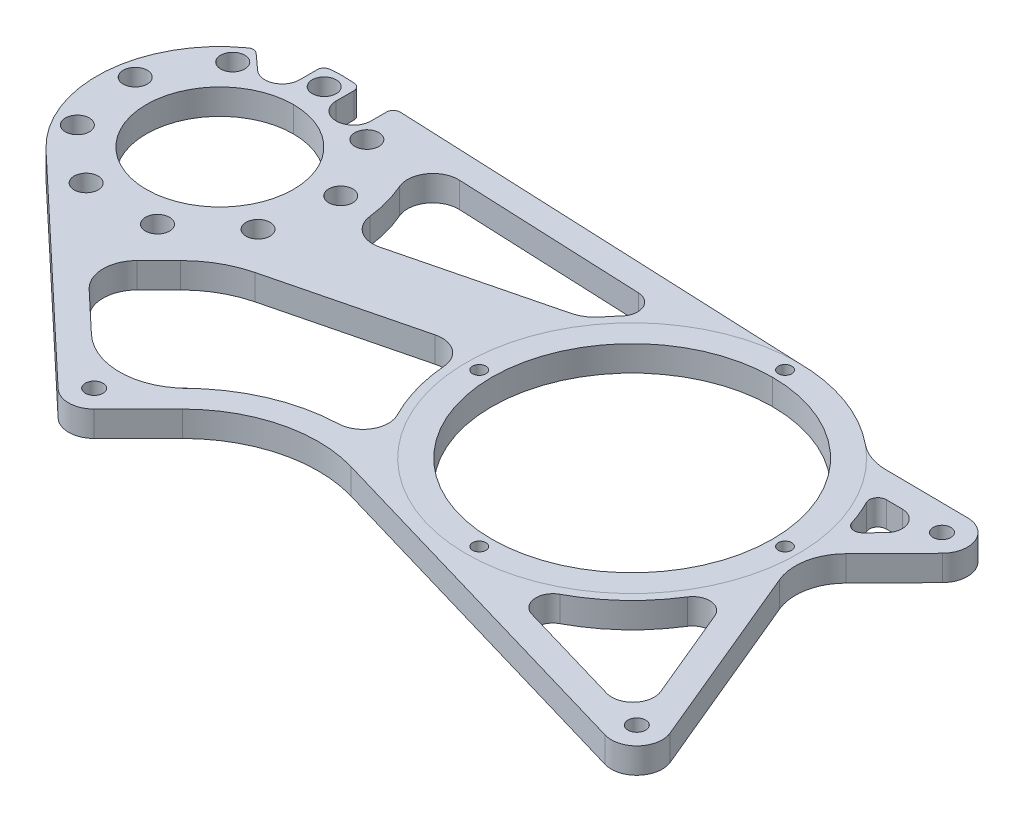
SolidWorks part; units mm, degrees
material "6061-T6 (SS)"
ref_plane "X-Y Datum" through (0, 0, 0) normal (0, 0, 1) x (1, 0, 0)
ref_plane "X-Z Datum" through (0, 0, 0) normal (0, 1, 0) x (1, 0, 0)
ref_plane "Y-Z Datum" through (0, 0, 0) normal (1, 0, 0) x (0, 0, -1)
sketch "Master Sketch " plane through (0, 0, 0) normal (0, 1, 0) x (1, 0, 0)
  line L0 (0, 0) -> (116.84, 0) construction
  line L1 (0, 0) -> (-54.61, 0) construction
  line L2 (116.84, 0) -> (228.6, 0) construction
  line L3 (228.6, 0) -> (228.6, 146.8882) construction
  line L4 (123.19, 0) -> (123.19, 103.3018) construction
  line L5 (-54.61, 0) -> (-414.02, 0) construction
  line L6 (-54.61, 0) -> (-54.61, 127) construction
  line L7 (123.19, 155.7528) -> (123.19, 165.2778) construction
  line L8 (123.19, 103.3018) -> (228.6, 146.8882) construction
  line L9 (123.19, 103.3018) -> (228.6, 0) construction
  line L10 (0, 0) -> (123.19, 103.3018) construction
  line L11 (0, 0) -> (-54.61, 127) construction
  line L12 (-54.61, 127) -> (123.19, 103.3018) construction
  line L13 (-54.61, 127) -> (228.6, 146.8882) construction
  line L14 (0, 0) -> (0, 119.7213) construction
  line L15 (-86.1521, 93.553) -> (-6.535, 18.4704)
  line L16 (-54.61, 172.974) -> (123.19, 165.2778)
  line L17 (194.029, 112.3136) -> (211.9185, 130.5036)
  line L18 (174.2685, 147.0028) -> (205.2185, 146.707)
  line L19 (190.0247, 91.6331) -> (219.2522, 21.4395)
  line L20 (6.7352, 18.6648) -> (23.2432, 35.1728)
  line L21 (207.7804, 8.6376) -> (73.45, 48.0018)
  circle A0 centre (0, 0) radius 12.7 construction
  circle A1 centre (228.6, 146.8882) radius 12.7 construction
  circle A2 centre (228.6, 0) radius 12.7 construction
  circle A3 centre (-414.02, 0) radius 12.7 construction
  circle A4 centre (123.19, 103.3018) radius 52.451
  circle A5 centre (123.19, 103.3018) radius 57.15 construction
  circle A6 centre (123.19, 103.3018) radius 61.976 construction
  circle A7 centre (-54.61, 127) radius 45.974
  circle A8 centre (-54.61, 127) radius 39 construction
  circle A9 centre (205.1275, 137.1825) radius 3 construction
  circle A10 centre (210.459, 17.7782) radius 3 construction
  circle A11 centre (0, 25.4) radius 3 construction
  circle A12 centre (0, 25.4) radius 9.525
  circle A13 centre (210.459, 17.7782) radius 9.525
  circle A14 centre (205.1275, 137.1825) radius 9.525
  arc A17 (56.7218, 112.1611) -> (171.0823, 56.3674) centre (123.19, 103.3018) ccw construction
  arc A18 (123.19, 165.2778) -> (162.3987, 151.2987) centre (123.19, 103.3018) cw
  circle A19 centre (123.19, 103.3018) radius 67.056 construction
  arc A20 (194.029, 112.3136) -> (190.0247, 91.6331) centre (207.611, 98.9558) ccw
  arc A21 (174.2685, 147.0028) -> (162.3987, 151.2987) centre (174.4505, 166.0519) cw
  arc A22 (73.45, 48.0018) -> (23.2432, 35.1728) centre (59.1643, -0.7482) ccw
  circle A23 centre (-54.61, 127) radius 25.908 construction
  circle A24 centre (-54.61, 127) radius 27.4955
  circle A25 centre (123.19, 160.4518) radius 2.5 construction
  circle A26 centre (-41.2712, 163.648) radius 6.5
  circle A27 centre (-67.9488, 163.648) radius 6.5
  point P9 (123.19, 0)
  point P23 (-54.61, 166)
  point P27 (-41.2712, 163.648)
  point P28 (-29.5413, 156.8757)
  point P29 (-20.835, 146.5)
  point P30 (-16.2025, 133.7723)
  point P31 (-16.2025, 120.2277)
  point P32 (-20.835, 107.5)
  point P33 (-29.5413, 97.1243)
  point P34 (-41.2712, 90.352)
  point P35 (-54.61, 88)
  point P36 (-67.9488, 90.352)
  point P37 (-79.6787, 97.1243)
  point P38 (-88.385, 107.5)
  point P39 (-93.0175, 120.2277)
  point P40 (-93.0175, 133.7723)
  point P41 (-88.385, 146.5)
  point P42 (-79.6787, 156.8757)
  point P43 (-67.9488, 163.648)
  point P44 (-54.61, 127)
  point P66 (190.246, 116.0018)
  point P74 (185.166, 103.3018)
  point P77 (167.0675, 147.0716)
  point P80 (71.8084, 60.2154)
  dimension "D1" = 105.41
  dimension "D2" = 25.4
  dimension "D8" = 103.3018
  dimension "D11" = 104.902
  dimension "D12" = 114.3
  dimension "D13" = 123.952
  dimension "D14" = 91.948
  dimension "D15" = 78
  dimension "D17" = 6
  dimension "D21" = 19.05
  dimension "D23" = 13
  dimension "D25" = 19.05
  dimension "D26" = 19.05
  dimension "D27" = 50.8
  dimension "D28" = 1.5875
  dimension "D30" = 51.816
  dimension "D31" = 5
  dimension "D3" = 146.8882
  dimension "D4" = 171.45
  dimension "D5" = 111.76
  dimension "D6" = 116.84
  dimension "D7" = 54.61
  dimension "D9" = 642.62
  dimension "D10" = 127
  dimension "D18" = 25.4
  dimension "D19" = 25.4
  dimension "D20" = 25.4
  dimension "D22" = 228.6
  dimension "D29" = 45
  dimension "D24" = 5.08
  dimension "D16" = 18
extrude "Boss-Extrude2" add sketch "Master Sketch " along normal mid plane 9.525 contours A22 L21 A13 L19 A20 L17 A14 L18 A21 A18 L16 A7 L15 A12 L20 A4 | A13 | A12 | A14 | L16 A7 A27 A26 A24
hole_wizard "Ø5.0mm Dowel Hole1" positions "Sketch26" profile "Sketch27" hole size "Ø5.0" standard "ANSI Metric" end condition through all
sketch "Sketch26" plane through (0, 4.7625, 0) normal (0, 1, 0) x (1, 0, 0)
  point P5 (123.19, 160.4518)
sketch "Sketch27" plane through (123.19, 4.7625, -160.4518) normal (1, 0, 0) x (0, 0, 1)
  line L0 (0, 0) -> (0, 9.525)
  line L1 (0, 9.525) -> (2.5, 9.525)
  line L2 (2.5, 9.525) -> (2.5, 0)
  line L5 (2.5, 0) -> (0, 0)
  line L11 (0, -6.35) -> (0, 107.95) construction
  dimension "Thru Hole Dia." = 5
  dimension "Thru Hole Depth" = 9.525
pattern_circular "CirPattern4" count 4 over 360 about axis through (123.19, 0, -103.3018) along (0, 1, 0) of "Ø5.0mm Dowel Hole1"
hole_wizard "M6 Clearance Hole4" positions "Sketch20" profile "Sketch21" hole size "M6" standard "ANSI Metric" end condition through all
sketch "Sketch20" plane through (0, 4.7625, 0) normal (0, 1, 0) x (1, 0, 0)
  point P0 (205.1275, 137.1825)
  point P3 (210.459, 17.7782)
  point P6 (0, 25.4)
  point P9 (205.1275, 137.1825)
sketch "Sketch21" plane through (205.1275, 4.7625, -137.1825) normal (1, 0, 0) x (0, 0, 1)
  line L0 (0, 0) -> (0, 9.525)
  line L1 (0, 9.525) -> (3.3, 9.525)
  line L2 (3.3, 9.525) -> (3.3, 0)
  line L5 (3.3, 0) -> (0, 0)
  line L11 (0, -6.35) -> (0, 107.95) construction
  dimension "Thru Hole Dia." = 6.6
  dimension "Thru Hole Depth" = 9.525
hole_wizard "M8 Clearance Hole1" positions "Sketch24" profile "Sketch25" hole size "M8" standard "ANSI Metric" end condition through all
sketch "Sketch24" plane through (0, 4.7625, 0) normal (0, 1, 0) x (1, 0, 0)
  point P2 (-54.61, 166)
sketch "Sketch25" plane through (-54.61, 4.7625, -166) normal (1, 0, 0) x (0, 0, 1)
  line L0 (0, 0) -> (0, 9.525)
  line L1 (0, 9.525) -> (4.5, 9.525)
  line L2 (4.5, 9.525) -> (4.5, 0)
  line L5 (4.5, 0) -> (0, 0)
  line L11 (0, -6.35) -> (0, 107.95) construction
  dimension "Thru Hole Dia." = 9
  dimension "Thru Hole Depth" = 9.525
pattern_circular "CirPattern3" count 9 over 360 about axis through (-54.61, 0, -127) along (0, 1, 0) of "M8 Clearance Hole1"
ref_plane "Plane2" through (-54.61, 0, 0) normal (1, 0, 0) x (0, 0, -1)
ref_plane "Plane1" through (123.19, 0, 0) normal (1, 0, 0) x (0, 0, -1)
split line "Split Line2"
split line "Split Line3"
ref_point "Point2"
ref_point "Point3"
sketch "Sketch28" plane through (0, 4.7625, 0) normal (0, 1, 0) x (1, 0, 0)
  circle A0 centre (123.19, 103.3018) radius 61.976 construction
  circle A1 centre (123.19, 103.3018) radius 61.976
split line "Split Line4"
sketch "Topology 3" plane through (0, 4.7625, 0) normal (0, 1, 0) x (1, 0, 0)
  line L0 (154.9255, 34.0517) -> (194.5112, 22.4515)
  line L1 (204.071, 33.1198) -> (189.6405, 67.7764)
  line L2 (190.1774, 137.3253) -> (184.1568, 137.3828)
  line L3 (190.4223, 122.2303) -> (194.6441, 126.523)
  line L4 (187.2379, 118.9925) -> (205.1275, 137.1825) construction
  line L5 (17.4418, 42.8418) -> (16.508, 41.908)
  line L6 (-33.0328, 56.5514) -> (-17.9453, 42.3233)
  line L7 (123.19, 165.2778) -> (-54.61, 172.974)
  line L8 (-86.1521, 93.553) -> (-6.535, 18.4704)
  line L9 (6.7352, 18.6648) -> (23.2432, 35.1728)
  line L10 (73.45, 48.0018) -> (207.7804, 8.6376)
  line L11 (219.2522, 21.4395) -> (190.0247, 91.6331)
  line L12 (194.029, 112.3136) -> (211.9185, 130.5036)
  line L13 (205.2185, 146.707) -> (174.2685, 147.0028)
  line L14 (123.19, 165.2778) -> (-54.61, 172.974)
  line L15 (-86.1521, 93.553) -> (-6.535, 18.4704)
  line L16 (6.7352, 18.6648) -> (23.2432, 35.1728)
  line L17 (73.45, 48.0018) -> (207.7804, 8.6376)
  line L18 (219.2522, 21.4395) -> (190.0247, 91.6331)
  line L19 (194.029, 112.3136) -> (211.9185, 130.5036)
  line L20 (205.2185, 146.707) -> (174.2685, 147.0028)
  line L22 (-7.4578, 92.9346) -> (46.4558, 106.413)
  line L23 (70.8038, 158.0115) -> (0.9187, 161.0365)
  line L24 (7.6514, 124.4645) -> (64.7984, 138.7513)
  line L25 (-33.2997, 74.7712) -> (-25.158, 82.9129)
  line L26 (122.7781, 155.7617) -> (-55.0219, 163.4579) construction
  line L27 (-79.6171, 100.4826) -> (0, 25.4) construction
  line L28 (0, 25.4) -> (16.508, 41.908) construction
  line L29 (76.1285, 57.1424) -> (210.459, 17.7782) construction
  line L30 (210.459, 17.7782) -> (181.2315, 87.9718) construction
  line L32 (205.1275, 137.1825) -> (174.1775, 137.4782) construction
  line L40 (-83.9738, 95.8628) -> (-4.3566, 20.7802) construction
  line L41 (4.4901, 20.9099) -> (20.9982, 37.4179) construction
  line L42 (74.3428, 51.0487) -> (208.6733, 11.6844) construction
  line L43 (216.3211, 20.2191) -> (187.0936, 90.4127) construction
  line L44 (191.7653, 114.5399) -> (209.6549, 132.7299) construction
  line L45 (205.1882, 143.5322) -> (174.2381, 143.8279) construction
  line L46 (97.5803, 163.2084) -> (-54.6775, 169.7989) construction
  arc A0 (123.19, 41.3258) -> (182.1581, 84.2285) centre (123.19, 103.3018) ccw
  arc A1 (153.7342, 45.7544) -> (178.3975, 68.7073) centre (123.19, 103.3018) ccw
  arc A2 (174.8956, 137.4713) -> (183.7852, 116.3114) centre (123.19, 103.3018) cw
  arc A3 (181.2948, 132.7718) -> (185.1396, 123.4736) centre (123.19, 103.3018) cw
  arc A4 (57.1448, 59.543) -> (16.508, 41.908) centre (59.1643, -0.7482) ccw
  arc A7 (61.4889, 97.4712) -> (82.4046, 56.6373) centre (123.19, 103.3018) ccw
  arc A8 (162.3987, 151.2987) -> (174.2685, 147.0028) centre (174.4505, 166.0519) ccw
  arc A9 (123.19, 165.2778) -> (162.3987, 151.2987) centre (123.19, 103.3018) ccw
  arc A10 (-54.61, 172.974) -> (-86.1521, 93.553) centre (-54.61, 127) ccw
  arc A11 (-6.535, 18.4704) -> (6.7352, 18.6648) centre (0, 25.4) ccw
  arc A12 (73.45, 48.0018) -> (23.2432, 35.1728) centre (59.1643, -0.7482) ccw
  arc A13 (207.7804, 8.6376) -> (219.2522, 21.4395) centre (210.459, 17.7782) ccw
  arc A14 (194.029, 112.3136) -> (190.0247, 91.6331) centre (207.611, 98.9558) ccw
  arc A15 (211.9185, 130.5036) -> (205.2185, 146.707) centre (205.1275, 137.1825) ccw
  arc A16 (162.3987, 151.2987) -> (174.2685, 147.0028) centre (174.4505, 166.0519) ccw
  arc A17 (123.19, 165.2778) -> (162.3987, 151.2987) centre (123.19, 103.3018) ccw
  arc A18 (-54.61, 172.974) -> (-86.1521, 93.553) centre (-54.61, 127) ccw
  arc A19 (-6.535, 18.4704) -> (6.7352, 18.6648) centre (0, 25.4) ccw
  arc A20 (73.45, 48.0018) -> (23.2432, 35.1728) centre (59.1643, -0.7482) ccw
  arc A21 (207.7804, 8.6376) -> (219.2522, 21.4395) centre (210.459, 17.7782) ccw
  arc A22 (194.029, 112.3136) -> (190.0247, 91.6331) centre (207.611, 98.9558) ccw
  arc A23 (211.9185, 130.5036) -> (205.2185, 146.707) centre (205.1275, 137.1825) ccw
  arc A24 (58.2588, 97.9542) -> (65.2908, 73.4299) centre (123.19, 103.3018) ccw
  arc A26 (76.4684, 144.0218) -> (75.2413, 142.5694) centre (123.19, 103.3018) cw
  arc A27 (-4.1248, 132.6464) -> (-8.1959, 147.6488) centre (-54.61, 127) ccw
  arc A28 (76.1285, 57.1424) -> (16.508, 41.908) centre (59.1643, -0.7482) ccw construction
  arc A29 (58.328, 97.1725) -> (80.3152, 54.2467) centre (123.19, 103.3018) ccw construction
  arc A30 (97.5803, 163.2084) -> (174.2023, 143.8283) centre (123.19, 103.3018) ccw construction
  arc A31 (123.19, 38.1508) -> (185.179, 83.2514) centre (123.19, 103.3018) ccw construction
  arc A32 (177.5444, 139.2218) -> (186.8894, 116.9779) centre (123.19, 103.3018) cw construction
  arc A33 (204.071, 33.1198) -> (194.5112, 22.4515) centre (196.7433, 30.0687) cw
  arc A34 (189.6405, 67.7764) -> (178.3975, 68.7073) centre (183.7784, 65.3355) ccw
  arc A35 (153.7342, 45.7544) -> (154.9255, 34.0517) centre (156.7112, 40.1455) ccw
  arc A36 (185.1396, 123.4736) -> (190.4223, 122.2303) centre (188.1586, 124.4566) ccw
  arc A37 (184.1568, 137.3828) -> (181.2948, 132.7718) centre (184.1264, 134.208) ccw
  arc A38 (194.6441, 126.523) -> (190.1774, 137.3253) centre (190.1167, 130.9756) ccw
  arc A42 (46.4558, 106.413) -> (58.2588, 97.9542) centre (48.766, 97.1724) cw
  arc A43 (57.1448, 59.543) -> (65.2908, 73.4299) centre (56.8259, 69.0627) ccw
  arc A46 (0.9187, 161.0365) -> (-8.1959, 147.6488) centre (0.5067, 151.5204) ccw
  arc A47 (7.6514, 124.4645) -> (-4.1248, 132.6464) centre (5.3412, 133.7051) cw
  arc A50 (-33.2997, 74.7712) -> (-33.0328, 56.5514) centre (-24.3195, 65.7909) ccw
  arc A51 (-6.535, 18.4704) -> (6.7352, 18.6648) centre (0, 25.4) ccw
  arc A55 (-7.4578, 92.9346) -> (-25.158, 82.9129) centre (1.7828, 55.9721) ccw
  arc A59 (17.4418, 42.8418) -> (-17.9453, 42.3233) centre (-0.5187, 60.8023) cw
  arc A60 (162.3987, 151.2987) -> (123.19, 165.2778) centre (123.19, 103.3018) ccw construction
  arc A61 (75.206, 147.3721) -> (71.7462, 143.2792) centre (123.19, 103.3018) ccw
  arc A62 (174.2023, 143.8283) -> (174.2381, 143.8279) centre (174.4505, 166.0519) ccw
  arc A63 (71.7462, 143.2792) -> (64.7984, 138.7513) centre (61.7182, 151.0721) cw
  arc A64 (70.8038, 158.0115) -> (75.206, 147.3721) centre (70.5292, 151.6674) cw
  arc A67 (-54.6775, 169.7989) -> (-83.9738, 95.8628) centre (-54.61, 127) ccw construction
  arc A68 (74.3428, 51.0487) -> (20.9982, 37.4179) centre (59.1643, -0.7482) ccw construction
  arc A69 (208.6733, 11.6844) -> (216.3211, 20.2191) centre (210.459, 17.7782) ccw construction
  arc A70 (191.7653, 114.5399) -> (187.0936, 90.4127) centre (207.611, 98.9558) ccw construction
  arc A71 (209.6549, 132.7299) -> (205.1882, 143.5322) centre (205.1275, 137.1825) ccw construction
  point P69 (67.1188, 129.7035)
  point P70 (95.7533, 158.8738)
  point P97 (6.7352, 32.1352)
  dimension "D11" = 7.9375
  dimension "D12" = 6.35
  dimension "D13" = 12.7
  dimension "D14" = 6.35
  dimension "D15" = 25.4
  dimension "D16" = 38.1
  dimension "D17" = 9.525
  dimension "D18" = 65.151
  dimension "D19" = 65.151
  dimension "D21" = 9.525
  dimension "D22" = 9.525
  dimension "D23" = 12.7
  dimension "D24" = 6.35
  dimension "D25" = 50.8
  dimension "D27" = 65.151
  dimension "D20" = 26.924
  dimension "D26" = 52
  dimension "D1" = 0
  dimension "D2" = 9.525
  dimension "D3" = 3.175
  dimension "D4" = 9.525
  dimension "D5" = 3.175
  dimension "D6" = 9.525
  dimension "D7" = 9.525
  dimension "D8" = 3.175
  dimension "D9" = 9.525
  dimension "D10" = 3.175
extrude "Cut-Extrude2" cut sketch "Topology 3" against normal through all contours A59 L5 A4 A43 A24 A42 L22 A55 L25 A50 L6 | A64 L23 A46 A27 A47 L24 A63 A61 | A1 A35 L0 A33 L1 A34 | L3 A38 L2 A37 A3 A36
sketch "Sketch29" plane through (0, -4.7625, 0) normal (0, -1, 0) x (1, 0, 0)
  line L0 (-72.3056, -158.8243) -> (-79.7134, -165.5153)
  line L1 (-61.4488, -163.648) -> (-61.4488, -172.4625)
  line L2 (-47.7712, -163.648) -> (-47.7712, -172.678)
  line L3 (-34.7712, -163.648) -> (-34.7712, -172.1153)
  line L4 (-54.61, -172.974) -> (123.19, -165.2778) construction
  line L5 (-47.7712, -172.678) -> (-34.7712, -172.1153)
  circle A1 centre (-41.2712, -163.648) radius 6.5 construction
  circle A2 centre (-67.9488, -163.648) radius 6.5 construction
  circle A3 centre (-41.2712, -163.648) radius 6.5 construction
  circle A4 centre (-67.9488, -163.648) radius 6.5 construction
  arc A5 (-86.1521, -93.553) -> (-54.61, -172.974) centre (-54.61, -127) ccw construction
  arc A6 (-86.1521, -93.553) -> (-54.61, -172.974) centre (-54.61, -127) ccw construction
  arc A7 (-72.3056, -158.8243) -> (-61.4488, -163.648) centre (-67.9488, -163.648) ccw
  arc A8 (-61.4488, -172.4625) -> (-79.7134, -165.5153) centre (-54.61, -127) cw
  arc A9 (-47.7712, -163.648) -> (-34.7712, -163.648) centre (-41.2712, -163.648) ccw
  dimension "D1" = 7.4078
extrude "Cut-Extrude3" cut sketch "Sketch29" against normal through all
fillet "Fillet1" radius 2.54 4 edges at (-79.7134, 0, -165.5153) (-61.4488, 0, -172.4625) (-47.7712, 0, -172.678) (-34.7712, 0, -172.1153)
